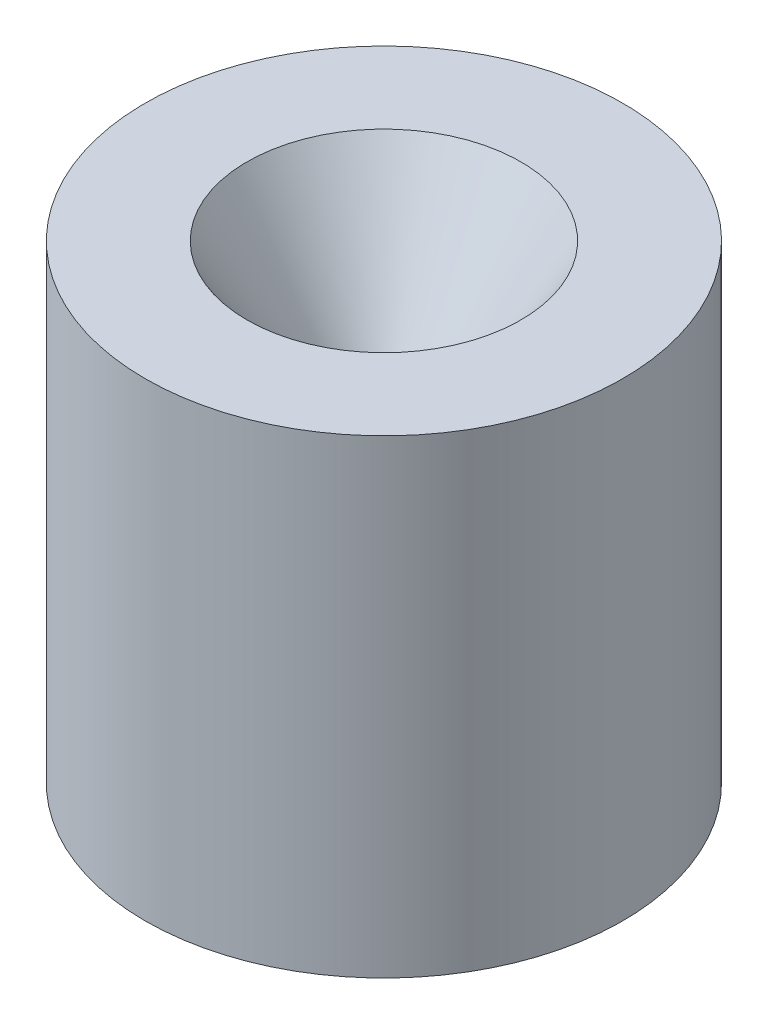
SolidWorks part; units mm, degrees
ref_plane "Спереди" through (0, 0, 0) normal (0, 0, 1) x (1, 0, 0)
ref_plane "Сверху" through (0, 0, 0) normal (0, 1, 0) x (1, 0, 0)
ref_plane "Справа" through (0, 0, 0) normal (1, 0, 0) x (0, 0, -1)
sketch "Эскиз1" plane through (0, 0, 0) normal (0, 1, 0) x (1, 0, 0)
  circle A0 centre (0, 0) radius 61
  dimension "D1" = 122
extrude "Бобышка-Вытянуть1" add sketch "Эскиз1" along normal blind 120
sketch "Эскиз2" plane through (0, 120, 0) normal (0, 1, 0) x (1, 0, 0)
  circle A0 centre (0, 0) radius 35
extrude "Вырез-Вытянуть1" cut sketch "Эскиз2" against normal blind 40 draft 32
